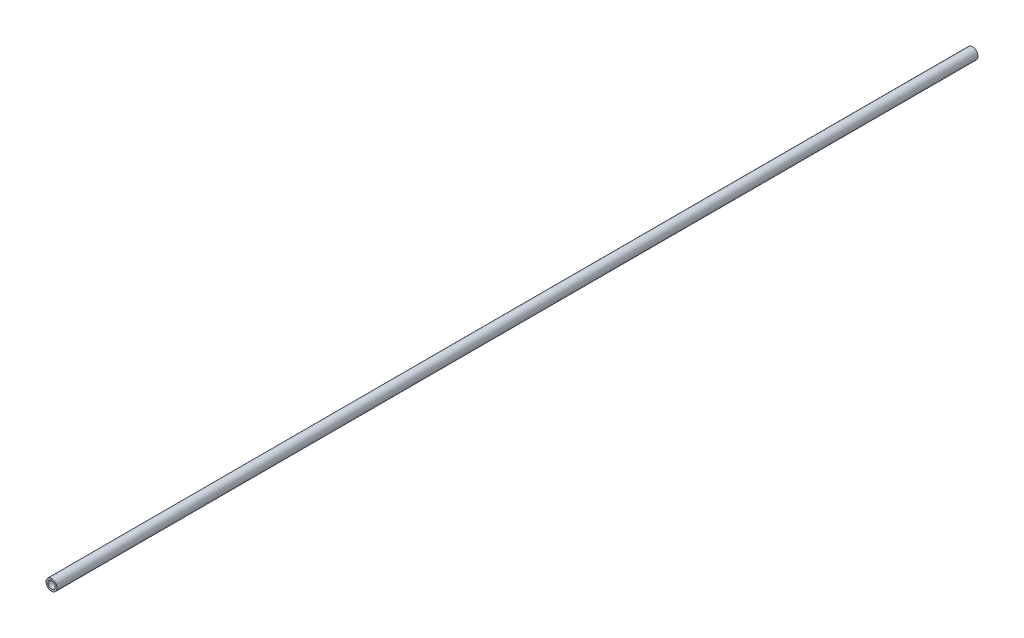
SolidWorks part; units mm, degrees
ref_plane "Face" through (0, 0, 0) normal (0, 0, 1) x (1, 0, 0)
ref_plane "Dessus" through (0, 0, 0) normal (0, 1, 0) x (1, 0, 0)
ref_plane "Droite" through (0, 0, 0) normal (1, 0, 0) x (0, 0, -1)
sketch "Esquisse1" plane through (0, 0, 0) normal (0, 0, 1) x (1, 0, 0)
  circle A0 centre (0, 0) radius 2
  circle A1 centre (0, 0) radius 3
  dimension "D1" = 1
  dimension "D2" = 6
extrude "Boss.-Extru.1" add sketch "Esquisse1" along normal blind 500
